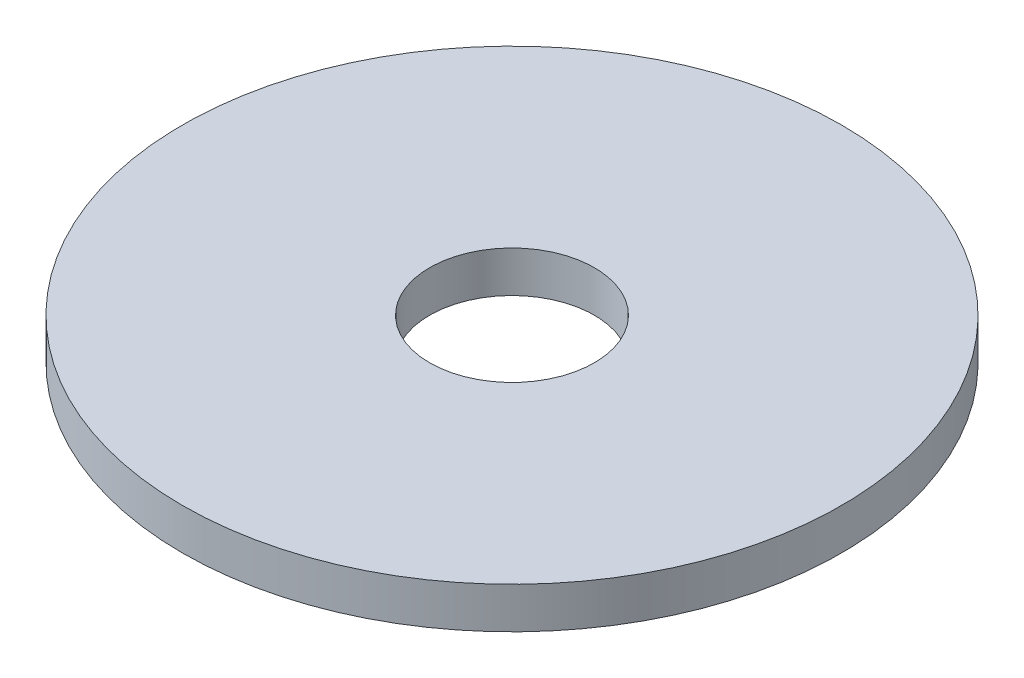
SolidWorks part; units mm, degrees
material "Nylon 101"
ref_plane "Front Plane" through (0, 0, 0) normal (0, 0, 1) x (1, 0, 0)
ref_plane "Top Plane" through (0, 0, 0) normal (0, 1, 0) x (1, 0, 0)
ref_plane "Right Plane" through (0, 0, 0) normal (1, 0, 0) x (0, 0, -1)
sketch "Sketch1" plane through (0, 0, 0) normal (0, 1, 0) x (1, 0, 0)
  circle A0 centre (0, 0) radius 12.7
  dimension "D1" = 25.4
extrude "Boss-Extrude1" add sketch "Sketch1" along normal blind 1.5875
sketch "Sketch2" plane through (0, 1.5875, 0) normal (0, 1, 0) x (1, 0, 0)
  circle A0 centre (0, 0) radius 3.175
  dimension "D1" = 6.35
extrude "Cut-Extrude1" cut sketch "Sketch2" against normal through all
